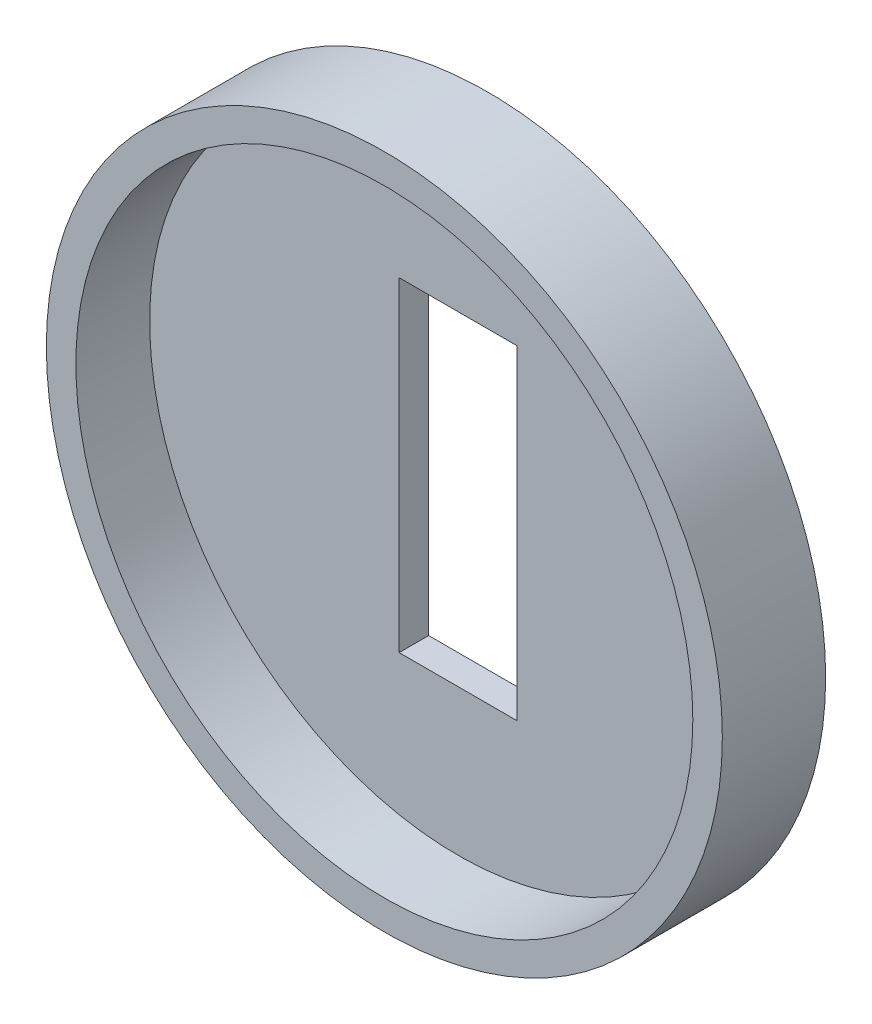
SolidWorks part; units mm, degrees
ref_plane "Ebene vorne" through (0, 0, 0) normal (0, 0, 1) x (1, 0, 0)
ref_plane "Ebene oben" through (0, 0, 0) normal (0, 1, 0) x (1, 0, 0)
ref_plane "Ebene rechts" through (0, 0, 0) normal (1, 0, 0) x (0, 0, -1)
sketch "Skizze1" plane through (0, 0, 0) normal (0, 1, 0) x (1, 0, 0)
  line L0 (0, 0) -> (22.902, 0)
  line L1 (22.902, 0) -> (22.902, -7)
  line L2 (22.902, -7) -> (20.902, -7)
  line L3 (20.902, -7) -> (20.902, -2)
  line L4 (20.902, -2) -> (0, -2)
  line L5 (0, -2) -> (0, 0)
revolve "Rotation2" add sketch "Skizze1" angle 360 about L5
sketch "Skizze2" plane through (0, 0, 0) normal (0, 0, -1) x (-1, 0, 0)
  line L0 (0, 0) -> (4, 0)
  line L4 (4, 11) -> (-4, 11)
  line L5 (-4, 11) -> (-4, -11)
  line L6 (4, 11) -> (4, -11)
  line L7 (4, -11) -> (-4, -11)
extrude "Schnitt-Linear austragen1" cut sketch "Skizze2" against normal blind 10
